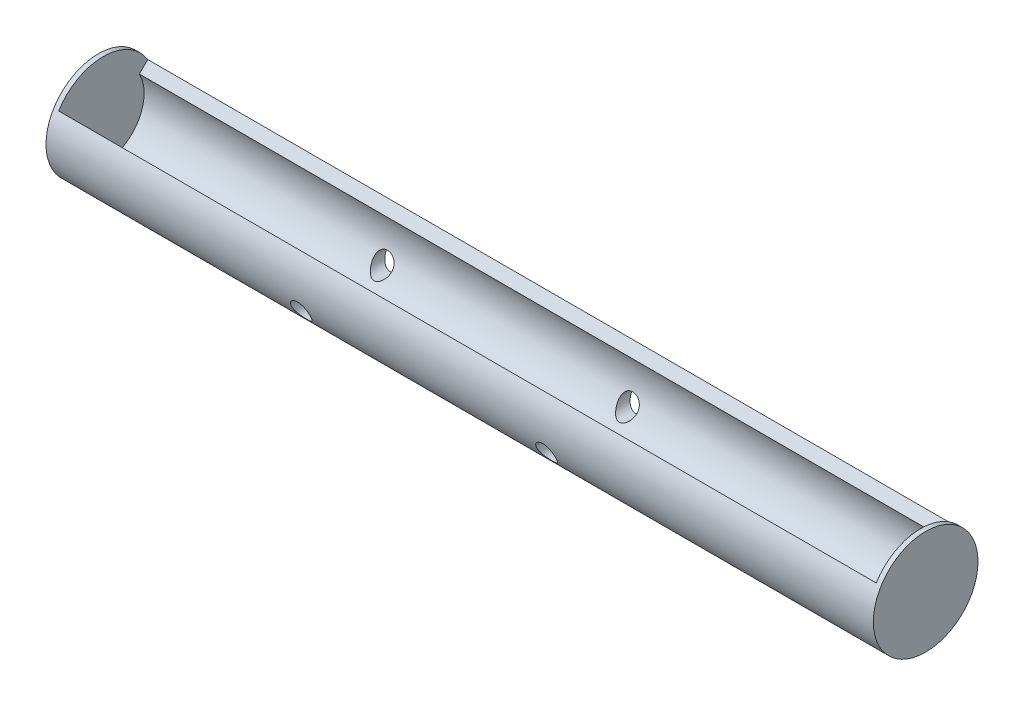
SolidWorks part; units mm, degrees
material "Plástico personalizado"
ref_plane "Plano frontal" through (0, 0, 0) normal (0, 0, 1) x (1, 0, 0)
ref_plane "Plano superior" through (0, 0, 0) normal (0, 1, 0) x (1, 0, 0)
ref_plane "Plano direito" through (0, 0, 0) normal (1, 0, 0) x (0, 0, -1)
sketch "Esboço1" plane through (0, 0, 0) normal (1, 0, 0) x (0, 0, -1)
  line L0 (0, 38.1135) -> (0, -38.5402) construction
  line L1 (-37.4371, 11.6578) -> (40.1211, 11.6578) construction
  line L2 (22.1155, 11.6578) -> (27.242, 16.7892)
  line L3 (-22.1155, 11.6578) -> (-27.2439, 16.786)
  arc A0 (-22.1155, 11.6578) -> (22.1155, 11.6578) centre (0, 0) ccw
  arc A1 (-27.2439, 16.786) -> (27.242, 16.7892) centre (0, 0) ccw
  dimension "D1" = 50
  dimension "D2" = 64
extrude "Ressalto-extrusão1" add sketch "Esboço1" along normal mid plane 500
ref_plane "Plano1" through (0, 0, 0) normal (0, 0, 1) x (1, 0, 0)
sketch "Esboço4" plane through (0, 0, 0) normal (0, 0, 1) x (1, 0, 0)
  line L0 (50, 36.7304) -> (50, -48.2571) construction
  line L1 (250, -32) -> (250, 16.7892) construction
  line L2 (-100, 36.7304) -> (-100, -48.2571) construction
  line L3 (-250, 16.7892) -> (-250, -32) construction
  circle A0 centre (50, -13.5251) radius 6
  circle A1 centre (-100, -13.5251) radius 6
  dimension "D3" = 12
  dimension "D4" = 12
  dimension "D1" = 200
  dimension "D2" = 150
extrude "Corte-extrusão2" cut sketch "Esboço4" against normal up to next and the other way up to next
sketch "Esboço5" plane through (250, 0, 0) normal (1, 0, 0) x (0, 0, -1)
  line L0 (-37.0755, 0) -> (39.4976, 0) construction
  circle A0 centre (0, 0) radius 32
extrude "Ressalto-extrusão2" add sketch "Esboço5" along normal blind 3
sketch "Esboço6" plane through (-250, 0, 0) normal (-1, 0, 0) x (0, 0, 1)
  line L0 (-35.6205, 0) -> (35.2393, 0) construction
  circle A0 centre (0, 0) radius 32
extrude "Ressalto-extrusão3" add sketch "Esboço6" along normal blind 3
